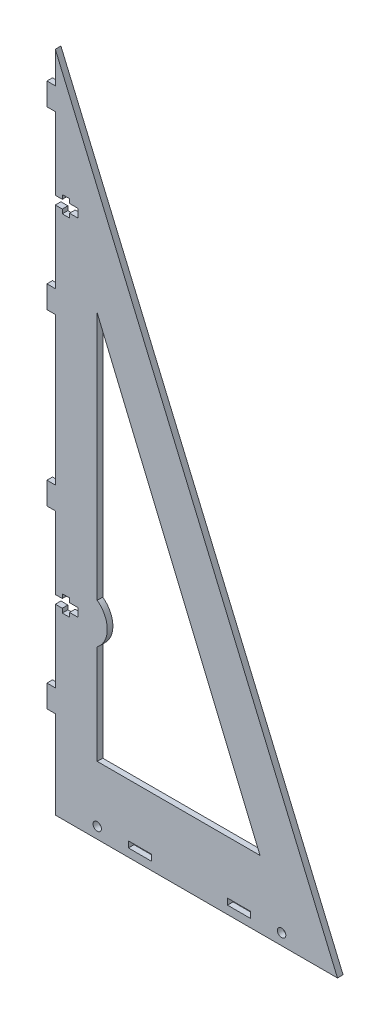
SolidWorks part; units mm, degrees
ref_plane "前视基准面" through (0, 0, 0) normal (0, 0, 1) x (1, 0, 0)
ref_plane "上视基准面" through (0, 0, 0) normal (0, 1, 0) x (1, 0, 0)
ref_plane "右视基准面" through (0, 0, 0) normal (1, 0, 0) x (0, 0, -1)
sketch "草图1" plane through (0, 0, 0) normal (0, 0, 1) x (1, 0, 0)
  line L18 (-45.726, 61.0274) -> (-45.726, 59.5274)
  line L35 (-22.076, -1.4476) -> (-13.876, -1.4476)
  line L36 (-13.876, 0.7524) -> (-13.876, -1.4476)
  line L37 (-22.076, 0.7524) -> (-13.876, 0.7524)
  line L38 (-22.076, 0.7524) -> (-22.076, -1.4476)
  line L63 (-48.226, 150.8399) -> (-48.226, 97.9649)
  line L91 (21.624, 0.7524) -> (21.624, -1.4476)
  line L92 (21.624, 0.7524) -> (13.424, 0.7524)
  line L93 (13.424, 0.7524) -> (13.424, -1.4476)
  line L96 (52.774, -4.3476) -> (19.524, -4.3476)
  line L124 (-17.976, -4.3476) -> (19.524, -4.3476)
  line L161 (21.624, -1.4476) -> (13.424, -1.4476)
  line L181 (-48.226, 221.7149) -> (-48.226, 233.0595)
  line L189 (-33.226, 158.8399) -> (25.0512, 19.7903)
  line L198 (-45.726, 64.0274) -> (-45.726, 65.5274)
  line L199 (-48.226, 35.0899) -> (-51.226, 35.0899)
  line L200 (-51.226, 35.0899) -> (-51.226, 27.0899)
  line L201 (-51.226, 27.0899) -> (-48.226, 27.0899)
  line L202 (-48.226, 27.0899) -> (-48.226, -4.3476)
  line L203 (-48.226, 64.0274) -> (-45.726, 64.0274)
  line L204 (-45.726, 59.5274) -> (-43.126, 59.5274)
  line L205 (-43.126, 59.5274) -> (-43.126, 61.0274)
  line L206 (-43.126, 61.0274) -> (-40.126, 61.0274)
  line L207 (-40.126, 64.0274) -> (-40.126, 61.0274)
  line L208 (-43.126, 64.0274) -> (-40.126, 64.0274)
  line L209 (-43.126, 65.5274) -> (-43.126, 64.0274)
  line L210 (-45.726, 65.5274) -> (-43.126, 65.5274)
  line L211 (-45.726, 61.0274) -> (-48.226, 61.0274)
  line L212 (-48.226, 64.0274) -> (-48.226, 61.0274) construction
  line L213 (-48.226, 62.5274) -> (-46.5987, 62.5274) construction
  line L214 (-48.226, 61.0274) -> (-48.226, 35.0899)
  line L215 (-48.226, 64.0274) -> (-48.226, 89.9649)
  line L216 (-51.226, 97.9649) -> (-48.226, 97.9649)
  line L217 (-51.226, 89.9649) -> (-51.226, 97.9649)
  line L218 (-48.226, 89.9649) -> (-51.226, 89.9649)
  line L219 (-45.726, 184.7774) -> (-45.726, 183.2774)
  line L220 (-45.726, 187.7774) -> (-45.726, 189.2774)
  line L221 (-48.226, 158.8399) -> (-51.226, 158.8399)
  line L222 (-51.226, 158.8399) -> (-51.226, 150.8399)
  line L223 (-51.226, 150.8399) -> (-48.226, 150.8399)
  line L224 (-48.226, 187.7774) -> (-45.726, 187.7774)
  line L225 (-45.726, 183.2774) -> (-43.126, 183.2774)
  line L226 (-43.126, 183.2774) -> (-43.126, 184.7774)
  line L227 (-43.126, 184.7774) -> (-40.126, 184.7774)
  line L228 (-40.126, 187.7774) -> (-40.126, 184.7774)
  line L229 (-43.126, 187.7774) -> (-40.126, 187.7774)
  line L230 (-43.126, 189.2774) -> (-43.126, 187.7774)
  line L231 (-45.726, 189.2774) -> (-43.126, 189.2774)
  line L232 (-45.726, 184.7774) -> (-48.226, 184.7774)
  line L233 (-48.226, 187.7774) -> (-48.226, 184.7774) construction
  line L234 (-48.226, 186.2774) -> (-46.5987, 186.2774) construction
  line L235 (-48.226, 184.7774) -> (-48.226, 158.8399)
  line L236 (-48.226, 187.7774) -> (-48.226, 213.7149)
  line L237 (-51.226, 221.7149) -> (-48.226, 221.7149)
  line L238 (-51.226, 213.7149) -> (-51.226, 221.7149)
  line L239 (-48.226, 213.7149) -> (-51.226, 213.7149)
  line L243 (25.0512, 19.7903) -> (-29.7988, 19.7903)
  line L246 (-29.7988, 19.7903) -> (-33.226, 19.7903)
  line L247 (-33.226, 19.7903) -> (-33.226, 27.0899)
  line L248 (-33.226, 69.7274) -> (-33.226, 158.8399)
  line L249 (-33.226, 27.0899) -> (-33.226, 55.3274)
  line L250 (-48.226, 233.0595) -> (52.774, -4.3476)
  line L251 (-17.976, -4.3476) -> (-48.226, -4.3476)
  circle A2 centre (-33.226, -0.3476) radius 1.5
  circle A47 centre (32.774, -0.3476) radius 1.5
  arc A54 (-33.226, 55.3274) -> (-33.226, 69.7274) centre (-38.626, 62.5274) ccw
  point P142 (-40.126, 62.5274)
  point P163 (-40.126, 186.2774)
extrude "凸台-拉伸1" add sketch "草图1" along normal blind 2
